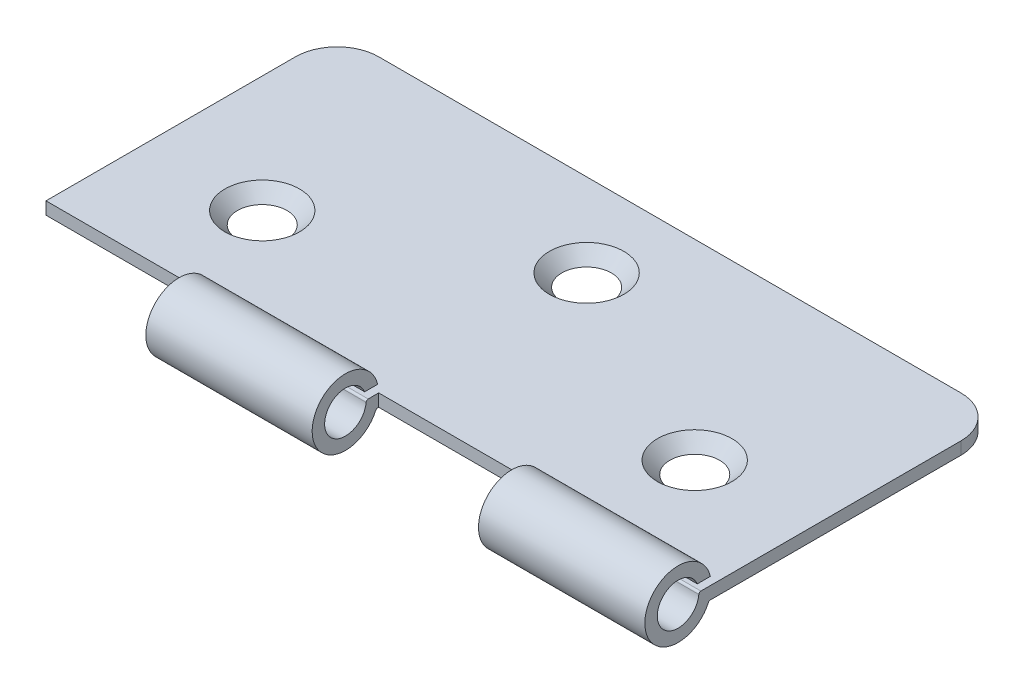
SolidWorks part; units mm, degrees
ref_plane "Front Plane" through (0, 0, 0) normal (0, 0, 1) x (1, 0, 0)
ref_plane "Top Plane" through (0, 0, 0) normal (0, 1, 0) x (1, 0, 0)
ref_plane "Right Plane" through (0, 0, 0) normal (1, 0, 0) x (0, 0, -1)
sketch "Sketch1" plane through (0, 0, 0) normal (0, 1, 0) x (1, 0, 0)
  line L1 (-40, -17.5) -> (40, -17.5)
  line L2 (-40, -17.5) -> (-40, 12.5)
  line L3 (-35, 17.5) -> (35, 17.5)
  line L4 (40, -17.5) -> (40, 12.5)
  line L5 (-40, -17.5) -> (40, 17.5) construction
  line L6 (-40, 17.5) -> (40, -17.5) construction
  arc A0 (35, 17.5) -> (40, 12.5) centre (35, 12.5) cw
  arc A1 (-35, 17.5) -> (-40, 12.5) centre (-35, 12.5) ccw
  point P0 (0, 0)
  dimension "D3" = 5
  dimension "D1" = 80
  dimension "D2" = 35
extrude "Boss-Extrude1" add sketch "Sketch1" along normal blind 1.5
sketch "Sketch2" plane through (40, 0, 0) normal (1, 0, 0) x (0, 0, -1)
  line L0 (-17.6161, 2.4567) -> (-19.1903, 2.4567)
  line L1 (-17.627, 0) -> (-17.5, 0)
  line L2 (-17.5, 0) -> (-17.5, 1.5)
  line L3 (-17.5, 1.5) -> (-18.7614, 1.5)
  arc A0 (-17.6161, 2.4567) -> (-17.8548, -0.1471) centre (-21.5, 1.5) ccw
  arc A1 (-19.1903, 2.4567) -> (-19.0104, 1.2727) centre (-21.5, 1.5) ccw
  arc A2 (-17.627, 0) -> (-17.8548, -0.1471) centre (-17.627, -0.25) ccw
  arc A3 (-19.0104, 1.2727) -> (-18.7614, 1.5) centre (-18.7614, 1.25) cw
  point P11 (-19, 1.5)
  dimension "D1" = 8
  dimension "D2" = 5
  dimension "D3" = 0.25
extrude "Boss-Extrude2" add sketch "Sketch2" against normal blind 20
pattern_linear "LPattern1" count 2 spacing 40 along (-1, 0, 0) of "Boss-Extrude2"
sketch "Sketch3" plane through (0, 1.5, 0) normal (0, 1, 0) x (1, 0, 0)
  line L0 (40, -18.7614) -> (40, 12.5) construction
  line L2 (0, -17.5) -> (20, -17.5) construction
  line L3 (35, 17.5) -> (-35, 17.5) construction
  line L4 (-40, 12.5) -> (-40, -17.5) construction
  point P0 (-26, -5.5)
  point P1 (0, 7.5)
  point P2 (26, -5.5)
  point P7 (28.3647, -17.6161)
  point P8 (0, 0)
  point P9 (0, 0)
  point P11 (0, 0)
  point P14 (0, 0)
  point P15 (0, 0)
  dimension "D1" = 14
  dimension "D2" = 12
  dimension "D3" = 10
  dimension "D4" = 14
hole_wizard "CSK for M4 SFHCS1" positions "Sketch4" profile "Sketch5" countersink size "M4" standard "ANSI Metric" end condition through all
sketch "Sketch4" plane through (0, 1.5, 0) normal (0, 1, 0) x (1, 0, 0)
  point P0 (-26, -5.5)
  point P3 (0, 7.5)
  point P6 (26, -5.5)
sketch "Sketch5" plane through (-26, 1.5, 5.5) normal (1, 0, 0) x (0, 0, 1)
  line L0 (0, 0) -> (0, 4)
  line L1 (0, 4) -> (2.25, 4)
  line L2 (2.25, 4) -> (2.25, 2.23)
  line L3 (2.25, 2.23) -> (4.48, 0)
  line L5 (4.48, 0) -> (0, 0)
  line L6 (-2.25, 2.23) -> (-4.48, 0) construction
  line L11 (0, -6.35) -> (0, 107.95) construction
  dimension "Thru Hole Dia." = 4.5
  dimension "Thru Hole Depth" = 4
  dimension "Near C'Sink Dia." = 8.96
  dimension "Near C'Sink Angle" = 90
